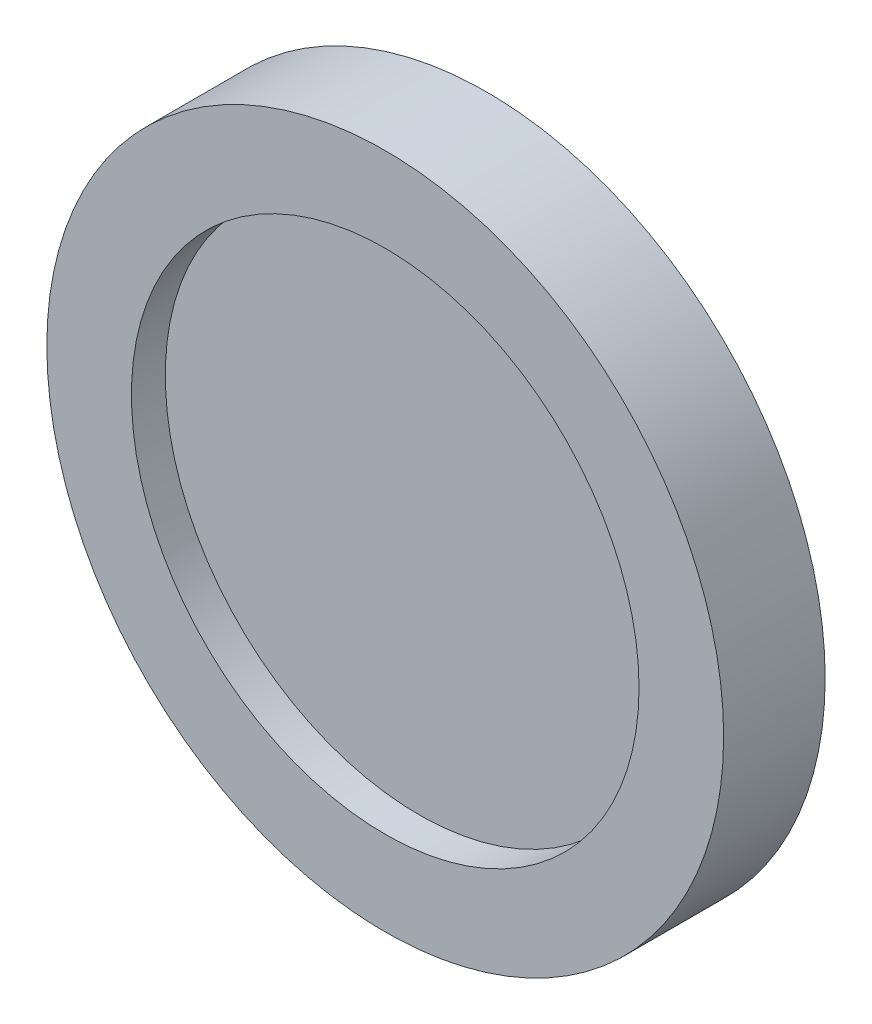
SolidWorks part; units mm, degrees
ref_plane "Front Plane" through (0, 0, 0) normal (0, 0, 1) x (1, 0, 0)
ref_plane "Top Plane" through (0, 0, 0) normal (0, 1, 0) x (1, 0, 0)
ref_plane "Right Plane" through (0, 0, 0) normal (1, 0, 0) x (0, 0, -1)
sketch "Sketch1" plane through (0, 0, 0) normal (0, 0, 1) x (1, 0, 0)
  circle A0 centre (0, 0) radius 100
extrude "Boss-Extrude1" add sketch "Sketch1" along normal blind 30
sketch "Sketch2" plane through (0, 0, 30) normal (0, 0, 1) x (1, 0, 0)
  circle A0 centre (0, 0) radius 75
extrude "Cut-Extrude1" cut sketch "Sketch2" against normal blind 10 contours A0
